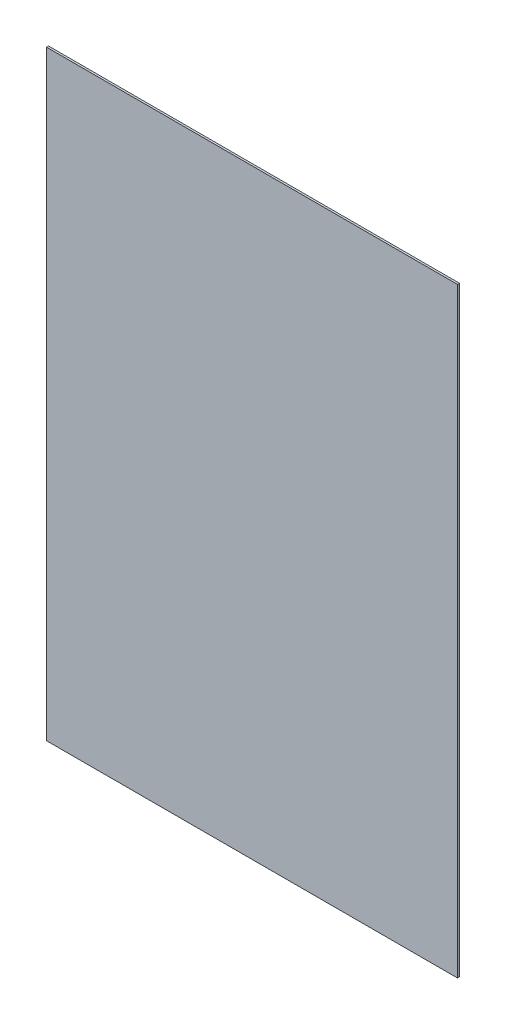
SolidWorks part; units mm, degrees
ref_plane "Front Plane" through (0, 0, 0) normal (0, 0, 1) x (1, 0, 0)
ref_plane "Top Plane" through (0, 0, 0) normal (0, 1, 0) x (1, 0, 0)
ref_plane "Right Plane" through (0, 0, 0) normal (1, 0, 0) x (0, 0, -1)
sketch "Sketch2" plane through (0, 0, 0) normal (0, 0, 1) x (1, 0, 0)
  line L1 (-324.765, 474.765) -> (324.765, 474.765)
  line L2 (-324.765, 474.765) -> (-324.765, -474.765)
  line L3 (-324.765, -474.765) -> (324.765, -474.765)
  line L4 (324.765, 474.765) -> (324.765, -474.765)
  line L5 (-324.765, 474.765) -> (324.765, -474.765) construction
  line L6 (-324.765, -474.765) -> (324.765, 474.765) construction
  point P0 (0, 0)
  dimension "Length 1" = 649.53
  dimension "Length 2" = 949.53
extrude "Boss-Extrude1" add sketch "Sketch2" along normal blind 3.175
